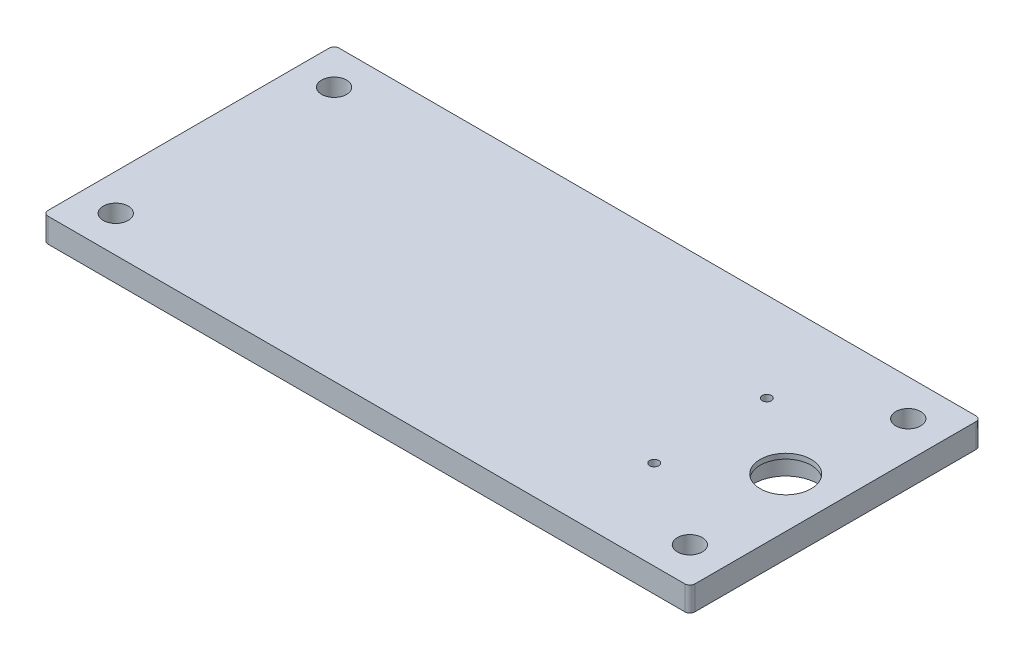
SolidWorks part; units mm, degrees
ref_plane "Front Plane" through (0, 0, 0) normal (0, 0, 1) x (1, 0, 0)
ref_plane "Top Plane" through (0, 0, 0) normal (0, 1, 0) x (1, 0, 0)
ref_plane "Right Plane" through (0, 0, 0) normal (1, 0, 0) x (0, 0, -1)
sketch "Sketch1" plane through (0, 0, 0) normal (0, 1, 0) x (1, 0, 0)
  line L1 (-127, -57.15) -> (127, -57.15)
  line L2 (-127, -57.15) -> (-127, 57.15)
  line L3 (-127, 57.15) -> (127, 57.15)
  line L4 (127, -57.15) -> (127, 57.15)
  line L5 (-127, -57.15) -> (127, 57.15) construction
  line L6 (-127, 57.15) -> (127, -57.15) construction
  point P0 (0, 0)
  dimension "D1" = 254
  dimension "D2" = 114.3
extrude "Boss-Extrude1" add sketch "Sketch1" along normal blind 9.525
sketch "Sketch2" plane through (0, 9.525, 0) normal (0, 1, 0) x (1, 0, 0)
  line L0 (127, -57.15) -> (127, 57.15) construction
  circle A0 centre (107.475, 0) radius 10
  dimension "D1" = 20
  dimension "D2" = 19.525
extrude "Cut-Extrude1" cut sketch "Sketch2" against normal through all contours A0
sketch "Sketch3" plane through (0, 9.525, 0) normal (0, 1, 0) x (1, 0, 0)
  point P0 (112.7125, 42.8625)
  point P1 (112.7125, -42.8675)
  point P3 (-112.7175, -42.8675)
  point P5 (-112.7175, 42.8625)
hole_wizard "3/8 Clearance Hole1" positions "Sketch3" profile "Sketch4" hole size "3/8" standard "ANSI Inch"
sketch "Sketch4" plane through (112.7125, 9.525, -42.8625) normal (1, 0, 0) x (0, 0, 1)
  line L0 (0, 0) -> (0, 12.9455)
  line L1 (0, 12.9455) -> (4.9022, 10)
  line L2 (4.9022, 10) -> (4.9022, 0)
  line L5 (4.9022, 0) -> (0, 0)
  line L10 (0, 12.9455) -> (-4.9022, 10) construction
  line L11 (0, -6.35) -> (0, 107.95) construction
  dimension "Hole Dia." = 9.8044
  dimension "Hole Depth" = 10
  dimension "Drill Angle" = 118
fillet "Fillet1" radius 2 4 edges at (127, 4.7625, 57.15) (-127, 4.7625, 57.15) (-127, 4.7625, -57.15) (127, 4.7625, -57.15)
sketch "Sketch8" plane through (0, 0, 0) normal (0, -1, 0) x (1, 0, 0)
  line L0 (67, -27.15) -> (88.9, -27.15) construction
  line L1 (67, -27.15) -> (67, 27.15) construction
  line L2 (88.9, -27.15) -> (88.9, 27.15) construction
  line L3 (67, 27.15) -> (88.9, 27.15) construction
  line L4 (67, -27.15) -> (88.9, 27.15) construction
  line L5 (88.9, -27.15) -> (67, 27.15) construction
  line L6 (127, 55.15) -> (127, -55.15) construction
  point P0 (77.95, 22.1)
  point P1 (77.95, 0)
  point P9 (77.95, -22.1)
  dimension "D1" = 21.9
  dimension "D2" = 54.3
  dimension "D3" = 38.1
  dimension "D4" = 44.2
  dimension "D5" = 10.95
  dimension "D6" = 5.05
hole_wizard "M3 Clearance Hole1" positions "Sketch8" profile "Sketch10" hole size "M3" standard "ANSI Metric"
sketch "Sketch10" plane through (77.95, 0, 22.1) normal (1, 0, 0) x (0, 0, -1)
  line L0 (0, 0) -> (0, 11.0815)
  line L1 (0, 11.0815) -> (1.8, 10)
  line L2 (1.8, 10) -> (1.8, 0)
  line L5 (1.8, 0) -> (0, 0)
  line L10 (0, 11.0815) -> (-1.8, 10) construction
  line L11 (0, -6.35) -> (0, 107.95) construction
  dimension "Hole Dia." = 3.6
  dimension "Hole Depth" = 10
  dimension "Drill Angle" = 118
sketch "Sketch11" plane through (0, 0, 0) normal (0, -1, 0) x (1, 0, 0)
  circle A0 centre (107.475, 0) radius 10 construction
  circle A1 centre (107.475, 0) radius 10
  circle A2 centre (107.475, 0) radius 12.5
  dimension "D1" = 2.5
extrude "Cut-Extrude2" cut sketch "Sketch11" against normal offset from surface (7.525 mm away) 2 up to face at (77.95, 9.525, 20.3)
